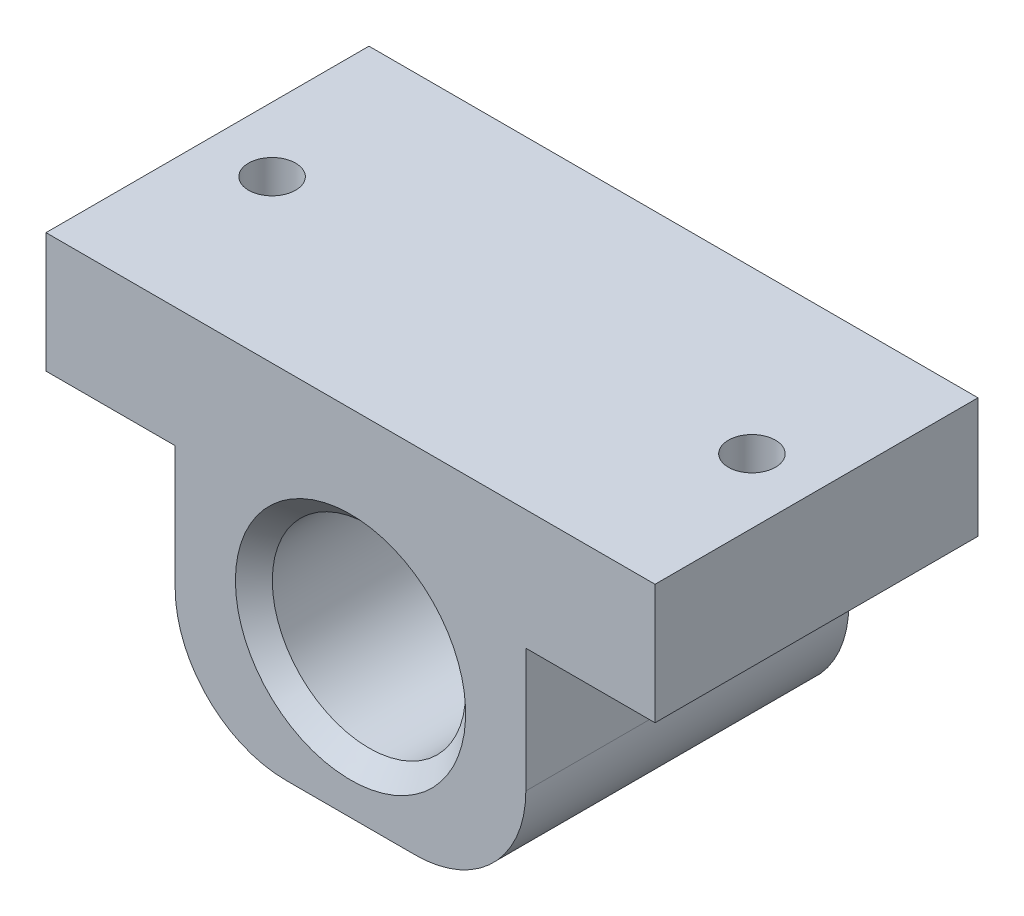
SolidWorks part; units mm, degrees
ref_plane "Alzado" through (0, 0, 0) normal (0, 0, 1) x (1, 0, 0)
ref_plane "Planta" through (0, 0, 0) normal (0, 1, 0) x (1, 0, 0)
ref_plane "Vista lateral" through (0, 0, 0) normal (1, 0, 0) x (0, 0, -1)
sketch "Croquis1" plane through (0, 0, 0) normal (0, 0, 1) x (1, 0, 0)
  line L0 (-33, 22.4) -> (33, 22.4)
  line L1 (33, 22.4) -> (33, 9.4)
  line L2 (33, 9.4) -> (19, 9.4)
  line L3 (19, 9.4) -> (19, -4)
  line L4 (7, -16) -> (-7, -16)
  line L5 (-19, -4) -> (-19, 9.4)
  line L6 (-19, 9.4) -> (-33, 9.4)
  line L7 (-33, 9.4) -> (-33, 22.4)
  line L8 (0, 0) -> (0, -16) construction
  line L9 (0, 22.4) -> (0, 10.475) construction
  circle A0 centre (0, 0) radius 10.475
  arc A1 (19, -4) -> (7, -16) centre (7, -4) cw
  arc A2 (-7, -16) -> (-19, -4) centre (-7, -4) cw
  point P6 (0, 22.4)
  dimension "D1" = 20.95
  dimension "D7" = 12
  dimension "D2" = 22.4
  dimension "D3" = 16
  dimension "D4" = 38
  dimension "D5" = 13
  dimension "D6" = 14
extrude "Saliente-Extruir1" add sketch "Croquis1" along normal blind 35
sketch "Croquis2" plane through (0, 9.4, 0) normal (0, -1, 0) x (1, 0, 0)
  line L0 (-26, 35) -> (-26, 0) construction
  line L1 (-33, 35) -> (-19, 35) construction
  line L2 (-33, 0) -> (-19, 0) construction
  line L3 (26, 35) -> (26, 0) construction
  line L4 (19, 35) -> (33, 35) construction
  line L5 (19, 0) -> (33, 0) construction
  circle A0 centre (-26, 17.5) radius 2.55
  circle A1 centre (26, 17.5) radius 2.55
  point P10 (26, 17.5)
  point P11 (-26, 17.5)
  dimension "D1" = 5.1
extrude "Cortar-Extruir1" cut sketch "Croquis2" against normal through all
chamfer "Chaflán1" distance 2 angle 45 2 edges at (10.475, 0, 0) (10.475, 0, 35)
sketch "Croquis3" plane through (0, -16, 0) normal (0, -1, 0) x (1, 0, 0)
  line L0 (0, 35) -> (0, 0) construction
  line L1 (-7, 35) -> (7, 35) construction
  circle A0 centre (0, 17.5) radius 1.375
  dimension "D1" = 2.75
extrude "Cortar-Extruir2" cut sketch "Croquis3" against normal up to next
